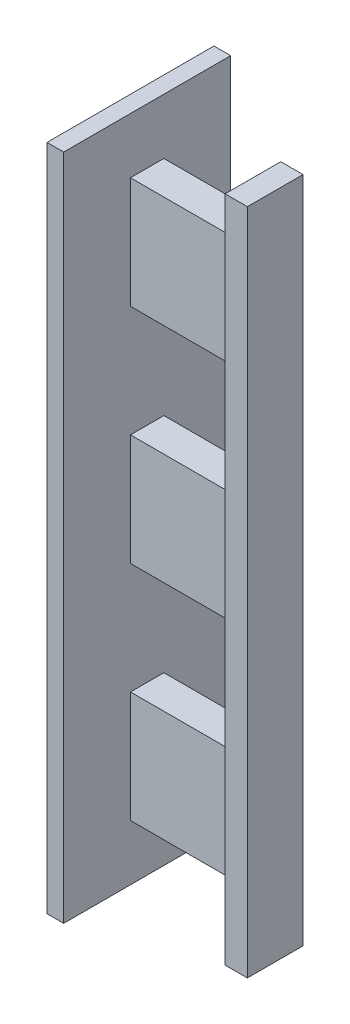
SolidWorks part; units mm, degrees
ref_plane "前视基准面" through (0, 0, 0) normal (0, 0, 1) x (1, 0, 0)
ref_plane "上视基准面" through (0, 0, 0) normal (0, 1, 0) x (1, 0, 0)
ref_plane "右视基准面" through (0, 0, 0) normal (1, 0, 0) x (0, 0, -1)
other "Configuration Table"
sketch "草图1" plane through (0, 0, 0) normal (1, 0, 0) x (0, 0, -1)
  line L0 (0, 31.9197) -> (0, -34.0629) construction
  line L1 (-3.5, -30) -> (1.5, -30)
  line L2 (-3.5, -30) -> (-3.5, 30)
  line L3 (-3.5, 30) -> (1.5, 30)
  line L4 (1.5, -30) -> (1.5, 30)
  line L5 (-3.5, -30) -> (1.5, 30) construction
  line L6 (-3.5, 30) -> (1.5, -30) construction
  line L7 (18.5819, 0) -> (-18.5363, 0) construction
  point P0 (-1, 0)
  point P7 (-2.3484, 1.6872)
  point P12 (0, 0)
  point P13 (0, 0)
  dimension "D1" = 60
  dimension "D2" = 5
  dimension "D3" = 1
extrude "凸台-拉伸1" add sketch "草图1" along normal blind 2
sketch "草图2" plane through (0, 0, 0) normal (-1, 0, 0) x (0, 0, 1)
  line L0 (0, -19.7323) -> (0, 23.6559) construction
  line L1 (-1.5, 25) -> (1.5, 25)
  line L2 (-1.5, -5) -> (1.5, -5)
  line L3 (-1.5, -5) -> (-1.5, 5)
  line L4 (-1.5, 5) -> (1.5, 5)
  line L5 (1.5, -5) -> (1.5, 5)
  line L6 (-1.5, -5) -> (1.5, 5) construction
  line L7 (-1.5, 5) -> (1.5, -5) construction
  line L8 (-1.5, 15) -> (-1.5, 25)
  line L9 (1.5, 15) -> (1.5, 25)
  line L10 (-1.5, 15) -> (1.5, 15)
  line L11 (-1.5, 5) -> (-1.5, 25) construction
  line L12 (-1.5, -15) -> (1.5, -15)
  line L13 (-1.5, -25) -> (-1.5, -15)
  line L14 (1.5, -25) -> (1.5, -15)
  line L15 (-1.5, -25) -> (1.5, -25)
  line L16 (-1.5, 5) -> (-1.5, -15) construction
  point P1 (0, 0)
  dimension "D1" = 10
  dimension "D2" = 3
  dimension "D4" = 20
  dimension "D6" = 20
  dimension "D3" = 2
  dimension "D5" = 2
extrude "凸台-拉伸2" add sketch "草图2" along normal blind 10.5
sketch "草图3" plane through (-10.5, 0, 0) normal (-1, 0, 0) x (0, 0, 1)
  line L1 (-7.5, -30) -> (7.5, -30)
  line L2 (-7.5, -30) -> (-7.5, 30)
  line L3 (-7.5, 30) -> (7.5, 30)
  line L4 (7.5, -30) -> (7.5, 30)
  line L5 (-7.5, -30) -> (7.5, 30) construction
  line L6 (-7.5, 30) -> (7.5, -30) construction
  point P0 (0, 0)
  dimension "D1" = 15
  dimension "D2" = 60
extrude "凸台-拉伸3" add sketch "草图3" along normal blind 1.5
